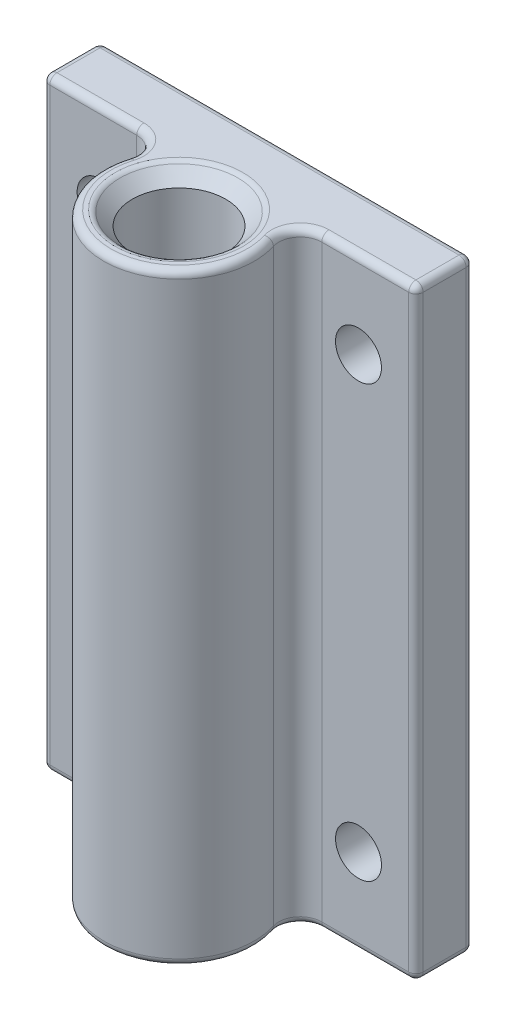
SolidWorks part; units mm, degrees
ref_plane "前视基准面" through (0, 0, 0) normal (0, 0, 1) x (1, 0, 0)
ref_plane "上视基准面" through (0, 0, 0) normal (0, 1, 0) x (1, 0, 0)
ref_plane "右视基准面" through (0, 0, 0) normal (1, 0, 0) x (0, 0, -1)
sketch "草图1" plane through (0, 0, 0) normal (0, 0, 1) x (1, 0, 0)
  line L0 (-13, 0) -> (13, 0) construction
  line L1 (13, -21) -> (-13, -21)
  line L2 (13, -21) -> (13, 21)
  line L3 (13, 21) -> (-13, 21)
  line L4 (-13, -21) -> (-13, 21)
  line L5 (13, -21) -> (-13, 21) construction
  line L6 (13, 21) -> (-13, -21) construction
  line L7 (0, 21) -> (0, -21) construction
  circle A2 centre (-9, 15) radius 1.6
  circle A3 centre (-9, -15) radius 1.6
  circle A4 centre (9, -15) radius 1.6
  circle A5 centre (9, 15) radius 1.6
  point P0 (0, 0)
  dimension "D1" = 3.2
  dimension "D2" = 30
  dimension "D3" = 18
  dimension "D4" = 4
  dimension "D5" = 6
extrude "凸台-拉伸1" add sketch "草图1" along normal blind 4
sketch "草图3" plane through (0, 0, 0) normal (0, 1, 0) x (1, 0, 0)
  line L0 (13, 0) -> (-13, 0) construction
  circle A0 centre (0, -7.5) radius 3.25
  circle A1 centre (0, -7.5) radius 5.25
  dimension "D1" = 6.5
  dimension "D2" = 2
  dimension "D3" = 7.5
extrude "凸台-拉伸2" add sketch "草图3" along normal mid plane 42
fillet "圆角1" radius 1.5 2 edges at (-3.9131, 0, 4) (3.9131, 0, 4)
chamfer "倒角1" distance 1 angle 45 2 edges at (0, 21, 10.75) (0, -21, 10.75)
fillet "圆角3" radius 0.5 22 edges at (0, -21, 0) (-9.7234, -21, 4) (-5.2393, -21, 4.6102) (0, -21, 12.75) (0, 21, 12.75) (5.2393, -21, 4.6102) (9.7234, -21, 4) (-4.25, -21, 7.5) (0, 21, 0) (9.7234, 21, 4) (5.2393, 21, 4.6102) (-5.2393, 21, 4.6102) (-9.7234, 21, 4) (4.25, 21, 7.5) (-13, 21, 2) (-13, 0, 4) (-13, -21, 2) (-13, 0, 0) (13, -21, 2) (13, 0, 4) (13, 21, 2) (13, 0, 0)
